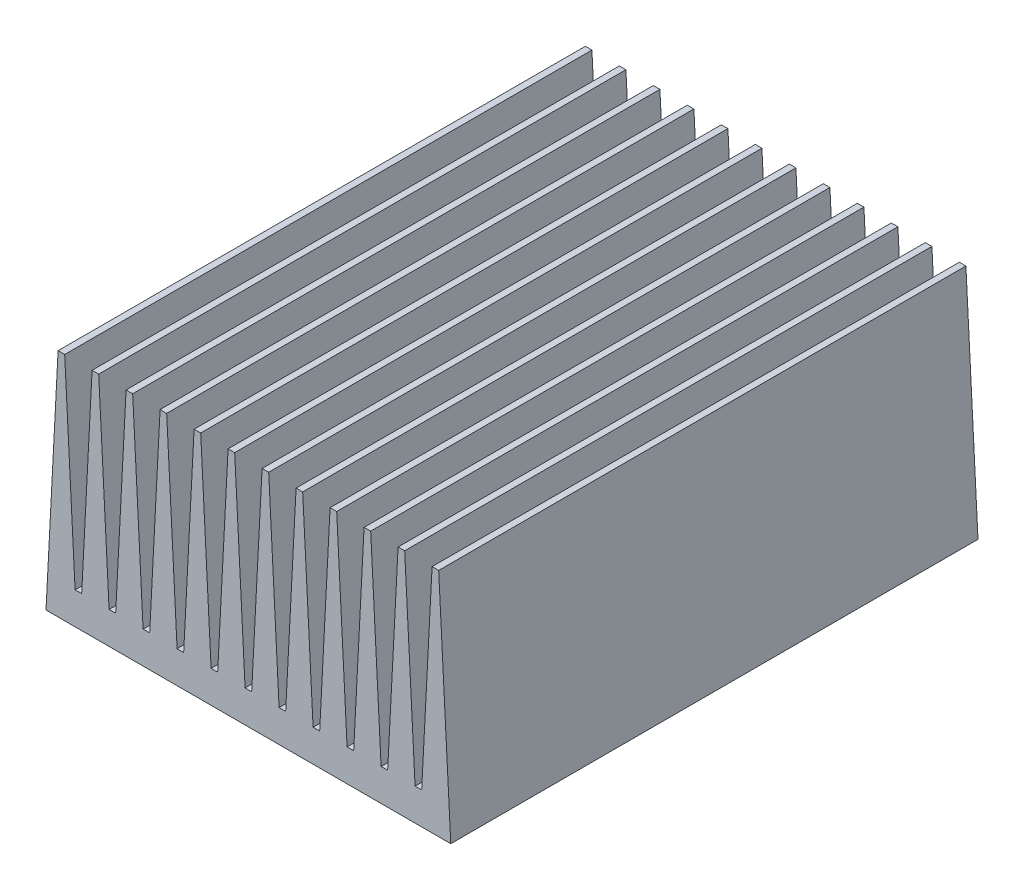
SolidWorks part; units mm, degrees
ref_plane "Płaszczyzna przednia" through (0, 0, 0) normal (0, 0, 1) x (1, 0, 0)
ref_plane "Płaszczyzna górna" through (0, 0, 0) normal (0, 1, 0) x (1, 0, 0)
ref_plane "Płaszczyzna prawa" through (0, 0, 0) normal (1, 0, 0) x (0, 0, -1)
sketch "Szkic1" plane through (0, 0, 0) normal (0, 0, 1) x (1, 0, 0)
  line L0 (-30.7082, 0) -> (30.7082, 0)
  line L1 (30.7082, 0) -> (28.8739, 35)
  line L2 (28.8739, 35) -> (27.8739, 35)
  line L3 (27.8739, 35) -> (26.2945, 4.8623)
  line L4 (26.2945, 4.8623) -> (25.2945, 4.8623)
  line L5 (30.7082, 0) -> (33.4225, 0) construction
  line L6 (28.8739, 35) -> (-21.2559, 35) construction
  line L7 (22.715, 35) -> (21.1356, 4.8623)
  line L8 (25.2945, 4.8623) -> (23.715, 35)
  line L9 (21.1356, 4.8623) -> (20.1356, 4.8623)
  line L10 (17.5561, 35) -> (15.9767, 4.8623)
  line L11 (20.1356, 4.8623) -> (18.5561, 35)
  line L12 (15.9767, 4.8623) -> (14.9767, 4.8623)
  line L13 (12.3972, 35) -> (10.8178, 4.8623)
  line L14 (14.9767, 4.8623) -> (13.3972, 35)
  line L15 (10.8178, 4.8623) -> (9.8178, 4.8623)
  line L16 (7.2383, 35) -> (5.6589, 4.8623)
  line L17 (9.8178, 4.8623) -> (8.2383, 35)
  line L18 (5.6589, 4.8623) -> (4.6589, 4.8623)
  line L19 (2.0794, 35) -> (0.5, 4.8623)
  line L20 (4.6589, 4.8623) -> (3.0794, 35)
  line L21 (0.5, 4.8623) -> (-0.5, 4.8623)
  line L22 (-3.0794, 35) -> (-4.6589, 4.8623)
  line L23 (-0.5, 4.8623) -> (-2.0794, 35)
  line L24 (-4.6589, 4.8623) -> (-5.6589, 4.8623)
  line L25 (-8.2383, 35) -> (-9.8178, 4.8623)
  line L26 (-5.6589, 4.8623) -> (-7.2383, 35)
  line L27 (-9.8178, 4.8623) -> (-10.8178, 4.8623)
  line L28 (-13.3972, 35) -> (-14.9767, 4.8623)
  line L29 (-10.8178, 4.8623) -> (-12.3972, 35)
  line L30 (-14.9767, 4.8623) -> (-15.9767, 4.8623)
  line L31 (-18.5561, 35) -> (-20.1356, 4.8623)
  line L32 (-15.9767, 4.8623) -> (-17.5561, 35)
  line L33 (-20.1356, 4.8623) -> (-21.1356, 4.8623)
  line L34 (-23.715, 35) -> (-25.2945, 4.8623)
  line L35 (-21.1356, 4.8623) -> (-22.715, 35)
  line L36 (-25.2945, 4.8623) -> (-26.2945, 4.8623)
  line L37 (-28.8739, 35) -> (-30.4534, 4.8623)
  line L38 (-26.2945, 4.8623) -> (-27.8739, 35)
  line L39 (-30.4534, 4.8623) -> (-30.7082, 0)
  line L40 (-30.4534, 4.8623) -> (-31.4534, 4.8623) [skipped]
  line L41 (-27.8739, 35) -> (-28.8739, 35)
  line L42 (-22.715, 35) -> (-23.715, 35)
  line L43 (-17.5561, 35) -> (-18.5561, 35)
  line L44 (-12.3972, 35) -> (-13.3972, 35)
  line L45 (-7.2383, 35) -> (-8.2383, 35)
  line L46 (-2.0794, 35) -> (-3.0794, 35)
  line L47 (3.0794, 35) -> (2.0794, 35)
  line L48 (7.2383, 35) -> (8.2383, 35)
  line L49 (12.3972, 35) -> (13.3972, 35)
  line L50 (17.5561, 35) -> (18.5561, 35)
  line L51 (22.715, 35) -> (23.715, 35)
  dimension "D1" = 35
  dimension "D2" = 93
  dimension "D3" = 1
  dimension "D4" = 87
  dimension "D5" = 1
  dimension "D6" = 4.8623
  dimension "D7" = 12
extrude "Dodanie-wyciągnięcie1" add sketch "Szkic1" against normal blind 80
